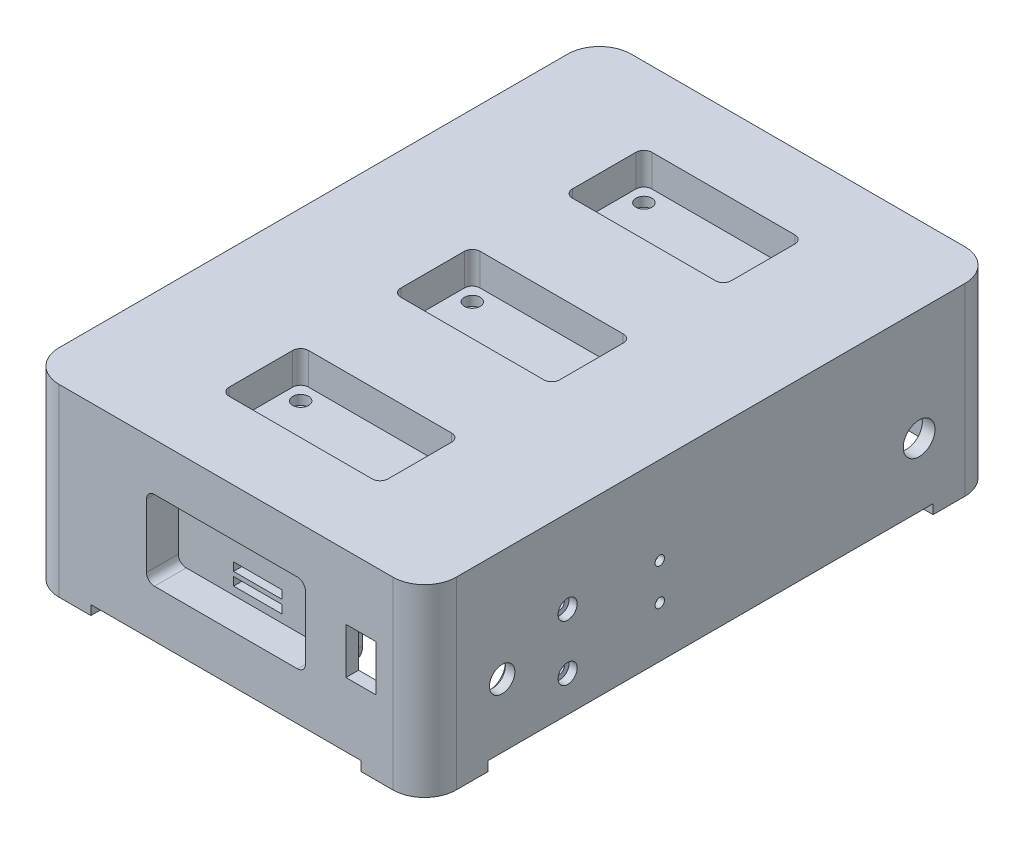
SolidWorks part; units mm, degrees
ref_plane "Спереди" through (0, 0, 0) normal (0, 0, 1) x (1, 0, 0)
ref_plane "Сверху" through (0, 0, 0) normal (0, 1, 0) x (1, 0, 0)
ref_plane "Справа" through (0, 0, 0) normal (1, 0, 0) x (0, 0, -1)
sketch "Эскиз1" plane through (0, 0, 0) normal (0, 1, 0) x (1, 0, 0)
  line L1 (-62.5, -90) -> (62.5, -90)
  line L2 (-62.5, -90) -> (-62.5, 90)
  line L3 (-62.5, 90) -> (62.5, 90)
  line L4 (62.5, -90) -> (62.5, 90)
  line L5 (-62.5, -90) -> (62.5, 90) construction
  line L6 (-62.5, 90) -> (62.5, -90) construction
  point P0 (0, 0)
  dimension "D1" = 125
  dimension "D2" = 180
extrude "Бобышка-Вытянуть1" add sketch "Эскиз1" along normal blind 55
sketch "Эскиз2" plane through (0, 0, 90) normal (0, 0, 1) x (1, 0, 0)
  line L0 (-1050, 27.5) -> (48950, 27.5) construction
  line L1 (-62.5, 55) -> (-62.5, 0) construction
  line L2 (0, -999.2777) -> (0, 49000.7223) construction
  line L4 (-22.5, 15) -> (22.5, 15)
  line L5 (-25, 17.5) -> (-25, 37.5)
  line L6 (-22.5, 40) -> (22.5, 40)
  line L7 (25, 17.5) -> (25, 37.5)
  line L8 (-25, 15) -> (25, 40) construction
  line L9 (-25, 40) -> (25, 15) construction
  arc A0 (-22.5, 40) -> (-25, 37.5) centre (-22.5, 37.5) ccw
  arc A1 (-25, 17.5) -> (-22.5, 15) centre (-22.5, 17.5) ccw
  arc A2 (25, 17.5) -> (22.5, 15) centre (22.5, 17.5) cw
  arc A3 (25, 37.5) -> (22.5, 40) centre (22.5, 37.5) ccw
  point P5 (-62.5, 27.5)
  point P6 (0, 27.5)
  dimension "D3" = 2.5
  dimension "D4" = 2.5
  dimension "D1" = 25
  dimension "D2" = 50
extrude "Вырез-Вытянуть1" cut sketch "Эскиз2" against normal blind 10
sketch "Эскиз4" plane through (0, 55, 0) normal (0, 1, 0) x (1, 0, 0)
  line L0 (0, -1000) -> (0, 49000) construction
  line L1 (-1000, 0) -> (49000, 0) construction
  line L2 (-22.5, 41.5) -> (22.5, 41.5)
  line L3 (-25, 44) -> (-25, 64)
  line L4 (-22.5, 66.5) -> (22.5, 66.5)
  line L5 (-22.5, -12.5) -> (22.5, -12.5)
  line L6 (-25, -10) -> (-25, 10)
  line L7 (-22.5, 12.5) -> (22.5, 12.5)
  line L8 (25, -10) -> (25, 10)
  line L9 (-25, -12.5) -> (25, 12.5) construction
  line L10 (-25, 12.5) -> (25, -12.5) construction
  line L11 (25, 44) -> (25, 64)
  line L12 (-25, 41.5) -> (25, 66.5) construction
  line L13 (-25, 66.5) -> (25, 41.5) construction
  line L14 (-25, -12.5) -> (25, -12.5) [skipped]
  line L15 (-25, -12.5) -> (-25, 12.5) [skipped]
  line L16 (-25, 12.5) -> (25, 12.5) [skipped]
  line L17 (25, -12.5) -> (25, 12.5) [skipped]
  line L18 (-25, -12.5) -> (25, 12.5) construction
  line L19 (-25, 12.5) -> (25, -12.5) construction
  line L20 (-22.5, -66.5) -> (22.5, -66.5)
  line L21 (-25, -64) -> (-25, -44)
  line L22 (-22.5, -41.5) -> (22.5, -41.5)
  line L23 (25, -64) -> (25, -44)
  line L24 (-25, -66.5) -> (25, -41.5) construction
  line L25 (-25, -41.5) -> (25, -66.5) construction
  arc A0 (22.5, -41.5) -> (25, -44) centre (22.5, -44) cw
  arc A1 (25, -64) -> (22.5, -66.5) centre (22.5, -64) cw
  arc A2 (-22.5, -66.5) -> (-25, -64) centre (-22.5, -64) cw
  arc A3 (-25, -44) -> (-22.5, -41.5) centre (-22.5, -44) cw
  arc A4 (-25, 64) -> (-22.5, 66.5) centre (-22.5, 64) cw
  arc A5 (-22.5, 12.5) -> (-25, 10) centre (-22.5, 10) ccw
  arc A6 (25, -10) -> (22.5, -12.5) centre (22.5, -10) cw
  arc A7 (22.5, 66.5) -> (25, 64) centre (22.5, 64) cw
  arc A8 (25, 44) -> (22.5, 41.5) centre (22.5, 44) cw
  arc A9 (-22.5, 41.5) -> (-25, 44) centre (-22.5, 44) cw
  arc A10 (22.5, 12.5) -> (25, 10) centre (22.5, 10) cw
  arc A11 (-22.5, -12.5) -> (-25, -10) centre (-22.5, -10) cw
  point P8 (0, 0)
  point P9 (0, 54)
  point P18 (0, 0)
  point P23 (0, -54)
  dimension "D7" = 2.5
  dimension "D8" = 2.5
  dimension "D1" = 25
  dimension "D2" = 50
  dimension "D5" = 41.5
  dimension "D6" = 41.5
  dimension "D3" = 2
  dimension "D4" = 2
extrude "Вырез-Вытянуть2" cut sketch "Эскиз4" against normal blind 10
mirror "Зеркальное отражение1" about plane through (0, 0, 0) normal (0, 0, 1) of "Вырез-Вытянуть1"
shell "Оболочка1" thickness 4
sketch "Эскиз5" plane through (-62.5, 0, 0) normal (-1, 0, 0) x (0, 0, 1)
  line L0 (45, 28.75) -> (45, 11.25) construction
  line L2 (90, 55) -> (90, 0) construction
  line L4 (-90, 0) -> (90, 0) construction
  line L7 (-1075, 20) -> (48925, 20) construction
  line L8 (-90, 55) -> (-90, 0) construction
  circle A3 centre (45, 28.75) radius 1.45
  circle A4 centre (45, 11.25) radius 1.45
  circle A5 centre (65.6, 20) radius 4
  circle A6 centre (-65.6, 20) radius 5
  dimension "D2" = 17.5
  dimension "D3" = 20
  dimension "D6" = 10
  dimension "D1" = 17.5
  dimension "D5" = 2.9
  dimension "D9" = 45
  dimension "D10" = 20.6
  dimension "D11" = 8
  dimension "D4" = 24.4
extrude "Вырез-Вытянуть3" cut sketch "Эскиз5" against normal blind 15
sketch "Эскиз6" plane through (-62.5, 0, 0) normal (-1, 0, 0) x (0, 0, 1)
  circle A2 centre (45, 28.75) radius 3
  circle A3 centre (45, 11.25) radius 3
  dimension "D1" = 6
extrude "Вырез-Вытянуть4" cut sketch "Эскиз6" against normal blind 2.5
sketch "Эскиз11" plane through (-58.5, 0, 0) normal (1, 0, 0) x (0, 0, -1)
  circle A1 centre (-65.6, 20) radius 5
  dimension "D1" = 10
extrude "Вырез-Вытянуть16" cut sketch "Эскиз11" against normal blind 1
mirror "Зеркальное отражение2" about plane through (0, 0, 0) normal (1, 0, 0) of "Вырез-Вытянуть3", "Вырез-Вытянуть4", "Вырез-Вытянуть16"
sketch "Эскиз12" plane through (0, 11, 0) normal (0, -1, 0) x (-1, 0, 0)
  line L0 (-1014.7864, -78) -> (48985.2136, -78) construction
  line L1 (22.5, -76) -> (-22.5, -76) construction
  line L2 (0, -1061) -> (0, 48939) construction
  line L3 (-10, -1061) -> (-10, 48939) construction
  line L4 (10, -1061) -> (10, 48939) construction
  circle A0 centre (-10, -78) radius 1.45
  circle A1 centre (10, -78) radius 1.45
  point P7 (0, -76)
  dimension "D4" = 2.9
  dimension "D1" = 2
  dimension "D2" = 20
  dimension "D3" = 10
extrude "Вырез-Вытянуть17" cut sketch "Эскиз12" against normal blind 14
sketch "Эскиз15" plane through (0, 45, 0) normal (0, 1, 0) x (1, 0, 0)
  line L0 (-1010.1672, -62.5) -> (48989.8328, -62.5) construction
  line L1 (0, -1031.5) -> (0, 48968.5) construction
  line L2 (-7.6, -63.8) -> (7.6, -63.8)
  line L3 (-7.6, -63.8) -> (-7.6, -61.2)
  line L4 (-7.6, -61.2) -> (7.6, -61.2)
  line L5 (7.6, -63.8) -> (7.6, -61.2)
  line L6 (-7.6, -63.8) -> (7.6, -61.2) construction
  line L7 (-7.6, -61.2) -> (7.6, -63.8) construction
  line L8 (22.5, -41.5) -> (-22.5, -41.5) construction
  line L9 (-22.5, -66.5) -> (22.5, -66.5) construction
  line L10 (-7.6, -9.8) -> (7.6, -9.8)
  line L11 (-7.6, -9.8) -> (-7.6, -7.2)
  line L12 (-7.6, -7.2) -> (7.6, -7.2)
  line L13 (7.6, -9.8) -> (7.6, -7.2)
  line L14 (-7.6, -9.8) -> (7.6, -7.2) construction
  line L15 (-7.6, -7.2) -> (7.6, -9.8) construction
  line L16 (-7.6, 44.2) -> (7.6, 44.2)
  line L17 (-7.6, 44.2) -> (-7.6, 46.8)
  line L18 (-7.6, 46.8) -> (7.6, 46.8)
  line L19 (7.6, 44.2) -> (7.6, 46.8)
  line L20 (-7.6, 44.2) -> (7.6, 46.8) construction
  line L21 (-7.6, 46.8) -> (7.6, 44.2) construction
  line L23 (22.5, 12.5) -> (-22.5, 12.5) construction
  line L24 (-7.6, -59.8) -> (7.6, -59.8)
  line L25 (-7.6, -59.8) -> (-7.6, -57.2)
  line L26 (-7.6, -57.2) -> (7.6, -57.2)
  line L27 (7.6, -59.8) -> (7.6, -57.2)
  line L28 (-7.6, -59.8) -> (7.6, -57.2) construction
  line L29 (-7.6, -57.2) -> (7.6, -59.8) construction
  line L30 (-7.6, -5.8) -> (7.6, -5.8)
  line L31 (-7.6, -5.8) -> (-7.6, -3.2)
  line L32 (-7.6, -3.2) -> (7.6, -3.2)
  line L33 (7.6, -5.8) -> (7.6, -3.2)
  line L34 (-7.6, -5.8) -> (7.6, -3.2) construction
  line L35 (-7.6, -3.2) -> (7.6, -5.8) construction
  line L36 (-7.6, 48.2) -> (7.6, 48.2)
  line L37 (-7.6, 48.2) -> (-7.6, 50.8)
  line L38 (-7.6, 50.8) -> (7.6, 50.8)
  line L39 (7.6, 48.2) -> (7.6, 50.8)
  line L40 (-7.6, 48.2) -> (7.6, 50.8) construction
  line L41 (-7.6, 50.8) -> (7.6, 48.2) construction
  line L42 (-22.5, -12.5) -> (22.5, -12.5) construction
  circle A0 centre (-20, -46.5) radius 2.5
  circle A1 centre (20, -46.5) radius 2.5
  circle A2 centre (-20, 7.5) radius 2.5
  circle A3 centre (20, 7.5) radius 2.5
  circle A4 centre (-20, 61.5) radius 2.5
  circle A5 centre (20, 61.5) radius 2.5
  point P1 (0, -62.5)
  point P12 (0, -41.5)
  point P16 (0, -8.5)
  point P21 (0, 45.5)
  point P41 (0, -4.5)
  point P42 (0, -58.5)
  point P51 (0, 49.5)
  dimension "D6" = 40
  dimension "D8" = 5
  dimension "D1" = 2.6
  dimension "D2" = 15.2
  dimension "D3" = 4
  dimension "D4" = 3
  dimension "D5" = 4
  dimension "D7" = 40
  dimension "D9" = 5
  dimension "D10" = 3
  dimension "D11" = 5
  dimension "D13" = 4
  dimension "D15" = 4
  dimension "D12" = 2
  dimension "D14" = 3
extrude "Вырез-Вытянуть20" cut sketch "Эскиз15" against normal blind 3
sketch "Эскиз16" plane through (0, 42, 0) normal (0, 1, 0) x (1, 0, 0)
  line L0 (-7.6, -62.5) -> (7.6, -62.5) construction
  line L1 (-7.6, -61.2) -> (-7.6, -63.8) construction
  line L2 (7.6, -63.8) -> (7.6, -61.2) construction
  line L3 (0, -1000) -> (0, 49000) construction
  line L4 (-7, -63.4) -> (7, -63.4)
  line L5 (-7, -63.4) -> (-7, -61.6)
  line L6 (-7, -61.6) -> (7, -61.6)
  line L7 (7, -63.4) -> (7, -61.6)
  line L8 (-7, -63.4) -> (7, -61.6) construction
  line L9 (-7, -61.6) -> (7, -63.4) construction
  line L10 (-7, -9.4) -> (7, -9.4)
  line L11 (-7, -9.4) -> (-7, -7.6)
  line L12 (-7, -7.6) -> (7, -7.6)
  line L13 (7, -9.4) -> (7, -7.6)
  line L14 (-7.6, -8.5) -> (7.6, -8.5) construction
  line L15 (-7, -9.4) -> (7, -7.6) construction
  line L16 (-7, -7.6) -> (7, -9.4) construction
  line L17 (-7, 44.6) -> (7, 44.6)
  line L18 (-7, 44.6) -> (-7, 46.4)
  line L19 (-7, 46.4) -> (7, 46.4)
  line L20 (7, 44.6) -> (7, 46.4)
  line L21 (-7.6, 45.5) -> (7.6, 45.5) construction
  line L22 (-7, 44.6) -> (7, 46.4) construction
  line L23 (-7, 46.4) -> (7, 44.6) construction
  line L24 (-7.6, -7.2) -> (-7.6, -9.8) construction
  line L25 (-7.6, -58.5) -> (7.6, -58.5) construction
  line L26 (-7, -59.4) -> (7, -59.4)
  line L27 (-7, -59.4) -> (-7, -57.6)
  line L28 (-7, -57.6) -> (7, -57.6)
  line L29 (7, -59.4) -> (7, -57.6)
  line L30 (-7, -59.4) -> (7, -57.6) construction
  line L31 (-7, -57.6) -> (7, -59.4) construction
  line L32 (-7.6, -57.2) -> (-7.6, -59.8) construction
  line L33 (7.6, -59.8) -> (7.6, -57.2) construction
  line L34 (-7.6, -4.5) -> (7.6, -4.5) construction
  line L35 (-7.6, -3.2) -> (-7.6, -5.8) construction
  line L36 (7.6, -5.8) -> (7.6, -3.2) construction
  line L37 (-7.6, -9.8) -> (7.6, -9.8) construction
  line L38 (-7, -5.4) -> (7, -5.4)
  line L39 (-7, -5.4) -> (-7, -3.6)
  line L40 (-7, -3.6) -> (7, -3.6)
  line L41 (7, -5.4) -> (7, -3.6)
  line L42 (-7, -5.4) -> (7, -3.6) construction
  line L43 (-7, -3.6) -> (7, -5.4) construction
  line L44 (7.6, -9.8) -> (7.6, -7.2) construction
  line L45 (-7.6, 46.8) -> (-7.6, 44.2) construction
  line L46 (7.6, 44.2) -> (7.6, 46.8) construction
  line L47 (-7.6, 44.2) -> (7.6, 44.2) construction
  line L48 (-7.6, 49.5) -> (7.6, 49.5) construction
  line L49 (-7.6, 50.8) -> (-7.6, 48.2) construction
  line L50 (7.6, 48.2) -> (7.6, 50.8) construction
  line L52 (-7, 48.6) -> (7, 48.6)
  line L53 (-7, 48.6) -> (-7, 50.4)
  line L54 (-7, 50.4) -> (7, 50.4)
  line L55 (7, 48.6) -> (7, 50.4)
  line L56 (-7, 48.6) -> (7, 50.4) construction
  line L57 (-7, 50.4) -> (7, 48.6) construction
  point P6 (0, -62.5)
  point P12 (0, -58.5)
  point P17 (0, -8.5)
  point P24 (0, 36.6)
  point P41 (0, -4.5)
  point P54 (0, 49.5)
  dimension "D1" = 1.8
  dimension "D2" = 14
  dimension "D4" = 0.4
  dimension "D3" = 0.4
extrude "Вырез-Вытянуть21" cut sketch "Эскиз16" against normal blind 3
sketch "Эскиз17" plane through (0, 0, 80) normal (0, 0, 1) x (1, 0, 0)
  line L0 (-7.6, 17.5) -> (7.6, 17.5)
  line L1 (-7.6, 17.5) -> (-7.6, 20.1)
  line L2 (-7.6, 20.1) -> (7.6, 20.1)
  line L3 (7.6, 17.5) -> (7.6, 20.1)
  line L4 (-7.6, 17.5) -> (7.6, 20.1) construction
  line L5 (-7.6, 20.1) -> (7.6, 17.5) construction
  line L7 (-7.6, 21.5) -> (7.6, 21.5)
  line L8 (-22.5, 15) -> (22.5, 15) construction
  line L9 (0, -965) -> (0, 49035) construction
  line L10 (22.5, 40) -> (-22.5, 40) construction
  line L11 (-7.6, 21.5) -> (-7.6, 24.1)
  line L12 (-7.6, 24.1) -> (7.6, 24.1)
  line L13 (7.6, 21.5) -> (7.6, 24.1)
  line L14 (-7.6, 21.5) -> (7.6, 24.1) construction
  line L15 (-7.6, 24.1) -> (7.6, 21.5) construction
  circle A0 centre (-20, 35) radius 2.5
  circle A1 centre (20, 35) radius 2.5
  point P0 (0, 18.8)
  point P11 (0, 22.8)
  point P20 (0, 40)
  dimension "D5" = 5
  dimension "D8" = 4
  dimension "D1" = 2.6
  dimension "D2" = 15.2
  dimension "D3" = 40
  dimension "D4" = 40
  dimension "D6" = 2.5
  dimension "D7" = 5
extrude "Вырез-Вытянуть22" cut sketch "Эскиз17" against normal blind 3
sketch "Эскиз18" plane through (0, 0, 77) normal (0, 0, 1) x (1, 0, 0)
  line L0 (-7.6, 18.8) -> (7.6, 18.8) construction
  line L1 (-7.6, 20.1) -> (-7.6, 17.5) construction
  line L2 (7.6, 17.5) -> (7.6, 20.1) construction
  line L3 (0, -980.9) -> (0, 49019.1) construction
  line L4 (-7, 17.9) -> (7, 17.9)
  line L5 (-7, 17.9) -> (-7, 19.7)
  line L6 (-7, 19.7) -> (7, 19.7)
  line L7 (7, 17.9) -> (7, 19.7)
  line L8 (-7, 17.9) -> (7, 19.7) construction
  line L9 (-7, 19.7) -> (7, 17.9) construction
  line L10 (7.6, 24.1) -> (-7.6, 24.1) construction
  line L12 (-7, 21.9) -> (7, 21.9)
  line L13 (-7, 21.9) -> (-7, 23.7)
  line L14 (-7, 23.7) -> (7, 23.7)
  line L15 (7, 21.9) -> (7, 23.7)
  line L16 (-7, 21.9) -> (7, 23.7) construction
  line L17 (-7, 23.7) -> (7, 21.9) construction
  point P6 (0, 18.8)
  point P12 (0, 22.8)
  point P16 (0, 24.1)
  dimension "D1" = 1.8
  dimension "D2" = 14
  dimension "D3" = 4
extrude "Вырез-Вытянуть23" cut sketch "Эскиз18" against normal blind 3
sketch "Эскиз19" plane through (0, 0, -80) normal (0, 0, -1) x (1, 0, 0)
  line L0 (-7.6, -37.5) -> (7.6, -37.5)
  line L1 (-7.6, -37.5) -> (-7.6, -34.9)
  line L2 (-7.6, -34.9) -> (7.6, -34.9)
  line L3 (7.6, -37.5) -> (7.6, -34.9)
  line L4 (-7.6, -37.5) -> (7.6, -34.9) construction
  line L5 (-7.6, -34.9) -> (7.6, -37.5) construction
  line L6 (0, -1010) -> (0, 48990) construction
  line L7 (-22.5, -15) -> (22.5, -15) construction
  line L9 (-7.6, -33.5) -> (7.6, -33.5)
  line L10 (22.5, -40) -> (-22.5, -40) construction
  line L11 (-7.6, -33.5) -> (-7.6, -30.9)
  line L12 (-7.6, -30.9) -> (7.6, -30.9)
  line L13 (7.6, -33.5) -> (7.6, -30.9)
  line L14 (-7.6, -33.5) -> (7.6, -30.9) construction
  line L15 (-7.6, -30.9) -> (7.6, -33.5) construction
  circle A0 centre (-20, -20) radius 2.5
  circle A1 centre (20, -20) radius 2.5
  point P0 (0, -36.2)
  point P14 (0, -15)
  point P16 (0, -32.2)
  dimension "D5" = 5
  dimension "D7" = 2.5
  dimension "D1" = 2.6
  dimension "D2" = 15.2
  dimension "D3" = 40
  dimension "D4" = 40
  dimension "D6" = 5
  dimension "D8" = 4
extrude "Вырез-Вытянуть24" cut sketch "Эскиз19" against normal blind 3
sketch "Эскиз20" plane through (0, 0, -77) normal (0, 0, -1) x (1, 0, 0)
  line L0 (-1007.6, -36.2) -> (48992.4, -36.2) construction
  line L1 (-7.6, -34.9) -> (-7.6, -37.5) construction
  line L3 (-7, -37.1) -> (7, -37.1)
  line L4 (-7, -37.1) -> (-7, -35.3)
  line L5 (-7, -35.3) -> (7, -35.3)
  line L6 (7, -37.1) -> (7, -35.3)
  line L7 (-7, -37.1) -> (7, -35.3) construction
  line L8 (-7, -35.3) -> (7, -37.1) construction
  line L9 (-7, -31.3) -> (7, -31.3)
  line L10 (0, -1029.9) -> (0, 48970.1) construction
  line L11 (7.6, -34.9) -> (-7.6, -34.9) construction
  line L12 (-7, -31.3) -> (-7, -33.1)
  line L13 (-7, -33.1) -> (7, -33.1)
  line L14 (7, -31.3) -> (7, -33.1)
  line L15 (-7, -31.3) -> (7, -33.1) construction
  line L16 (-7, -33.1) -> (7, -31.3) construction
  point P1 (0, -36.2)
  point P5 (-7.6, -36.2)
  point P10 (0, -32.2)
  point P18 (0, -34.9)
  dimension "D1" = 1.8
  dimension "D2" = 14
  dimension "D3" = 4
extrude "Вырез-Вытянуть25" cut sketch "Эскиз20" against normal blind 5
sketch "Эскиз21" plane through (0, 0, 90) normal (0, 0, -1) x (1, 0, 0)
  line L0 (-975, -27.5) -> (49025, -27.5) construction
  line L1 (37.75, -34.75) -> (47.25, -34.75)
  line L2 (37.75, -34.75) -> (37.75, -20.25)
  line L3 (37.75, -20.25) -> (47.25, -20.25)
  line L4 (47.25, -34.75) -> (47.25, -20.25)
  line L5 (37.75, -34.75) -> (47.25, -20.25) construction
  line L6 (37.75, -20.25) -> (47.25, -34.75) construction
  line L7 (25, -17.5) -> (25, -37.5) construction
  line L8 (42.5, -1022.5) -> (42.5, 48977.5) construction
  line L9 (62.5, -55) -> (62.5, 0) construction
  point P0 (42.5, -27.5)
  point P10 (25, -27.5)
  dimension "D1" = 9.5
  dimension "D2" = 14.5
  dimension "D3" = 20
extrude "Вырез-Вытянуть26" cut sketch "Эскиз21" along normal blind 4
sketch "Эскиз22" plane through (0, 0, 0) normal (0, -1, 0) x (-1, 0, 0)
  line L0 (-60.5, -925) -> (-60.5, 49075) construction
  line L2 (-62.5, -90) -> (-62.5, 90) construction
  line L3 (-1046.2998, 88) -> (48953.7002, 88) construction
  line L4 (-62.5, 90) -> (62.5, 90) construction
  line L5 (60.5, -925) -> (60.5, 49075) construction
  line L6 (62.5, 90) -> (62.5, -90) construction
  line L7 (-1052.5, -88) -> (48947.5, -88) construction
  line L8 (62.5, -90) -> (-62.5, -90) construction
  line L9 (0, -925) -> (0, 49075) construction
  line L10 (-1052.5, 0) -> (48947.5, 0) construction
  circle A4 centre (0, 88) radius 1.425
  circle A5 centre (0, -88) radius 1.425
  circle A6 centre (-60.5, 0) radius 1.425
  circle A7 centre (60.5, 0) radius 1.425
  point P27 (0, 90)
  point P34 (-62.5, 0)
  dimension "D5" = 2.85
  dimension "D1" = 2
  dimension "D2" = 2
  dimension "D3" = 2
  dimension "D4" = 2
extrude "Вырез-Вытянуть27" cut sketch "Эскиз22" against normal blind 9
sketch "Эскиз24" plane through (-62.5, 0, 0) normal (-1, 0, 0) x (0, 0, 1)
  line L0 (0, -1000) -> (0, 49000) construction
  line L1 (16, -988.2808) -> (16, 49011.7192) construction
  line L2 (-90, 0) -> (90, 0) construction
  circle A0 centre (16, 16) radius 1.475
  circle A1 centre (16, 27.5) radius 1.475
  dimension "D4" = 2.95
  dimension "D1" = 11.5
  dimension "D2" = 16
  dimension "D3" = 16
extrude "Вырез-Вытянуть28" cut sketch "Эскиз24" against normal through all
fillet "Скругление1" radius 10 4 edges at (62.5, 27.5, -90) (-62.5, 27.5, -90) (62.5, 27.5, 90) (-62.5, 27.5, 90)
sketch "Эскиз26" plane through (58.5, 0, 0) normal (-1, 0, 0) x (0, 0, 1)
  line L1 (17.6454, 18.85) -> (14.3546, 18.85)
  line L2 (14.3546, 18.85) -> (12.7091, 16)
  line L3 (12.7091, 16) -> (14.3546, 13.15)
  line L4 (14.3546, 13.15) -> (17.6454, 13.15)
  line L5 (17.6454, 13.15) -> (19.2909, 16)
  line L6 (19.2909, 16) -> (17.6454, 18.85)
  line L7 (17.6454, 30.35) -> (14.3546, 30.35)
  line L8 (14.3546, 30.35) -> (12.7091, 27.5)
  line L9 (12.7091, 27.5) -> (14.3546, 24.65)
  line L10 (14.3546, 24.65) -> (17.6454, 24.65)
  line L11 (17.6454, 24.65) -> (19.2909, 27.5)
  line L12 (19.2909, 27.5) -> (17.6454, 30.35)
  circle A0 centre (16, 16) radius 2.85 construction
  circle A1 centre (16, 27.5) radius 2.85 construction
  dimension "D1" = 5.7
extrude "Вырез-Вытянуть29" cut sketch "Эскиз26" against normal blind 2 and the other way blind 119
fillet "Скругление2" radius 3 4 edges at (58.5, 25.5, 86) (58.5, 25.5, -86) (-58.5, 25.5, -86) (-58.5, 25.5, 86)
sketch "Эскиз27" plane through (0, 0, 0) normal (0, -1, 0) x (1, 0, 0)
  line L0 (-52.5, -90) -> (-42.5, -90)
  line L1 (52.5, -90) -> (-52.5, -90) construction
  line L2 (-42.5, -90) -> (-42.5, -86)
  line L3 (55.5, -86) -> (-55.5, -86) construction
  line L4 (-42.5, -86) -> (-55.5, -86)
  line L6 (-58.5, -83) -> (-58.5, -70)
  line L7 (-58.5, -83) -> (-58.5, 83) construction
  line L8 (-58.5, -70) -> (-62.5, -70)
  line L9 (-62.5, -80) -> (-62.5, 80) construction
  line L10 (-62.5, -70) -> (-62.5, -80)
  line L11 (0, -1000) -> (0, 49000) construction
  line L12 (-1000, 0) -> (49000, 0) construction
  line L13 (62.5, -70) -> (62.5, -80)
  line L14 (58.5, -70) -> (62.5, -70)
  line L15 (58.5, -83) -> (58.5, -70)
  line L16 (42.5, -86) -> (55.5, -86)
  line L17 (42.5, -90) -> (42.5, -86)
  line L18 (52.5, -90) -> (42.5, -90)
  line L19 (52.5, 90) -> (42.5, 90)
  line L20 (42.5, 90) -> (42.5, 86)
  line L21 (42.5, 86) -> (55.5, 86)
  line L22 (58.5, 83) -> (58.5, 70)
  line L23 (58.5, 70) -> (62.5, 70)
  line L24 (62.5, 70) -> (62.5, 80)
  line L25 (-62.5, 70) -> (-62.5, 80)
  line L26 (-58.5, 70) -> (-62.5, 70)
  line L27 (-58.5, 83) -> (-58.5, 70)
  line L28 (-42.5, 86) -> (-55.5, 86)
  line L29 (-42.5, 90) -> (-42.5, 86)
  line L30 (-52.5, 90) -> (-42.5, 90)
  arc A1 (-62.5, -80) -> (-52.5, -90) centre (-52.5, -80) ccw construction
  arc A4 (58.5, -83) -> (55.5, -86) centre (55.5, -83) cw
  arc A5 (-62.5, -80) -> (-52.5, -90) centre (-52.5, -80) ccw
  arc A6 (62.5, -80) -> (52.5, -90) centre (52.5, -80) cw
  arc A7 (-58.5, 83) -> (-55.5, 86) centre (-55.5, 83) cw
  arc A8 (-58.5, -83) -> (-55.5, -86) centre (-55.5, -83) ccw construction
  arc A9 (-58.5, -83) -> (-55.5, -86) centre (-55.5, -83) ccw
  arc A10 (62.5, 80) -> (52.5, 90) centre (52.5, 80) ccw
  arc A11 (-62.5, 80) -> (-52.5, 90) centre (-52.5, 80) cw
  arc A12 (58.5, 83) -> (55.5, 86) centre (55.5, 83) ccw
  dimension "D1" = 10
extrude "Бобышка-Вытянуть2" add sketch "Эскиз27" along normal blind 3
sketch "Эскиз28" plane through (0, 0, 0) normal (0, -1, 0) x (1, 0, 0)
  line L0 (-58.5, 70) -> (-58.5, 83) construction
  line L2 (-58.5, 70) -> (-58.5, 83)
  line L3 (-55.5, 86) -> (-42.5, 86)
  line L4 (-42.5, 86) -> (-42.5, 86.5)
  line L5 (-42.5, 86) -> (-42.5, 90) construction
  line L6 (-42.5, 86.5) -> (-55.5, 86.5)
  line L7 (-1000, 0) -> (49000, 0) construction
  line L8 (-59, 83) -> (-59, 70)
  line L9 (-62.5, 70) -> (-58.5, 70) construction
  line L10 (-59, 70) -> (-58.5, 70)
  line L11 (0, -1000) -> (0, 49000) construction
  line L12 (59, 70) -> (58.5, 70)
  line L13 (59, 83) -> (59, 70)
  line L14 (42.5, 86.5) -> (55.5, 86.5)
  line L15 (42.5, 86) -> (42.5, 86.5)
  line L16 (55.5, 86) -> (42.5, 86)
  line L17 (58.5, 70) -> (58.5, 83)
  line L18 (58.5, -70) -> (58.5, -83)
  line L19 (55.5, -86) -> (42.5, -86)
  line L20 (42.5, -86) -> (42.5, -86.5)
  line L21 (42.5, -86.5) -> (55.5, -86.5)
  line L22 (59, -83) -> (59, -70)
  line L23 (59, -70) -> (58.5, -70)
  line L24 (-59, -70) -> (-58.5, -70)
  line L25 (-59, -83) -> (-59, -70)
  line L26 (-42.5, -86.5) -> (-55.5, -86.5)
  line L27 (-42.5, -86) -> (-42.5, -86.5)
  line L28 (-55.5, -86) -> (-42.5, -86)
  line L29 (-58.5, -70) -> (-58.5, -83)
  arc A0 (-55.5, 86) -> (-58.5, 83) centre (-55.5, 83) ccw construction
  arc A1 (-55.5, 86) -> (-58.5, 83) centre (-55.5, 83) ccw
  arc A2 (-59, 83) -> (-55.5, 86.5) centre (-55.5, 83) cw
  arc A3 (59, 83) -> (55.5, 86.5) centre (55.5, 83) ccw
  arc A4 (55.5, 86) -> (58.5, 83) centre (55.5, 83) cw
  arc A5 (55.5, -86) -> (58.5, -83) centre (55.5, -83) ccw
  arc A6 (59, -83) -> (55.5, -86.5) centre (55.5, -83) cw
  arc A7 (-59, -83) -> (-55.5, -86.5) centre (-55.5, -83) ccw
  arc A8 (-55.5, -86) -> (-58.5, -83) centre (-55.5, -83) cw
  dimension "D1" = 0.5
extrude "Вырез-Вытянуть30" cut sketch "Эскиз28" along normal blind 2.5
